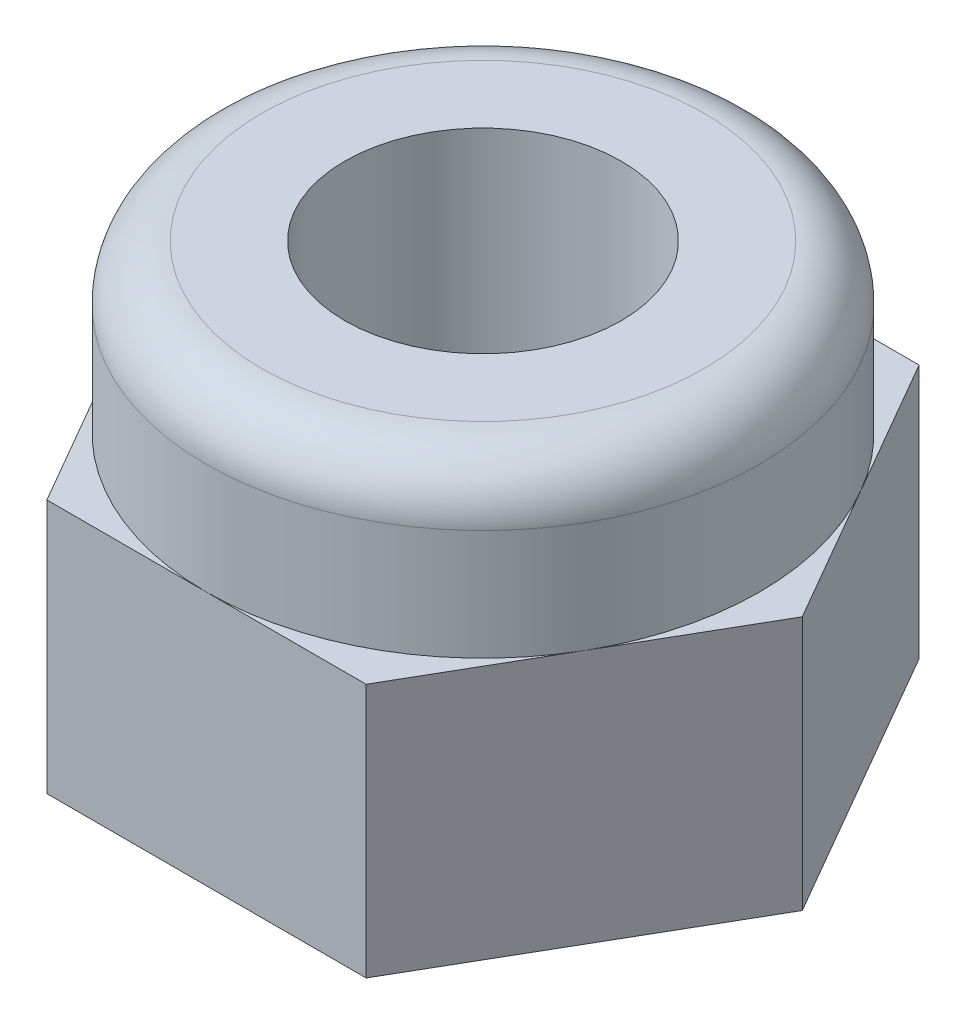
SolidWorks part; units mm, degrees
ref_plane "Plan de face" through (0, 0, 0) normal (0, 0, 1) x (1, 0, 0)
ref_plane "Plan de dessus" through (0, 0, 0) normal (0, 1, 0) x (1, 0, 0)
ref_plane "Plan de droite" through (0, 0, 0) normal (1, 0, 0) x (0, 0, -1)
sketch "Esquisse1" plane through (0, 0, 0) normal (0, 1, 0) x (1, 0, 0)
  line L1 (2.8868, 0) -> (1.4434, 2.5)
  line L2 (1.4434, 2.5) -> (-1.4434, 2.5)
  line L3 (-1.4434, 2.5) -> (-2.8868, 0)
  line L4 (-2.8868, 0) -> (-1.4434, -2.5)
  line L5 (-1.4434, -2.5) -> (1.4434, -2.5)
  line L6 (1.4434, -2.5) -> (2.8868, 0)
  circle A0 centre (0, 0) radius 2.5 construction
  circle A1 centre (0, 0) radius 1.25
  dimension "D1" = 5
  dimension "D2" = 2.5
extrude "Boss.-Extru.1" add sketch "Esquisse1" along normal blind 2.3
sketch "Esquisse2" plane through (0, 2.3, 0) normal (0, 1, 0) x (1, 0, 0)
  line L0 (1.4434, -2.5) -> (2.8868, 0) construction
  circle A0 centre (0, 0) radius 1.25
  circle A1 centre (0, 0) radius 1.25 construction
  circle A2 centre (0, 0) radius 2.5
extrude "Boss.-Extru.2" add sketch "Esquisse2" along normal blind 1.5
fillet "Congé1" radius 0.5 1 edges at (0, 3.8, 2.5)
